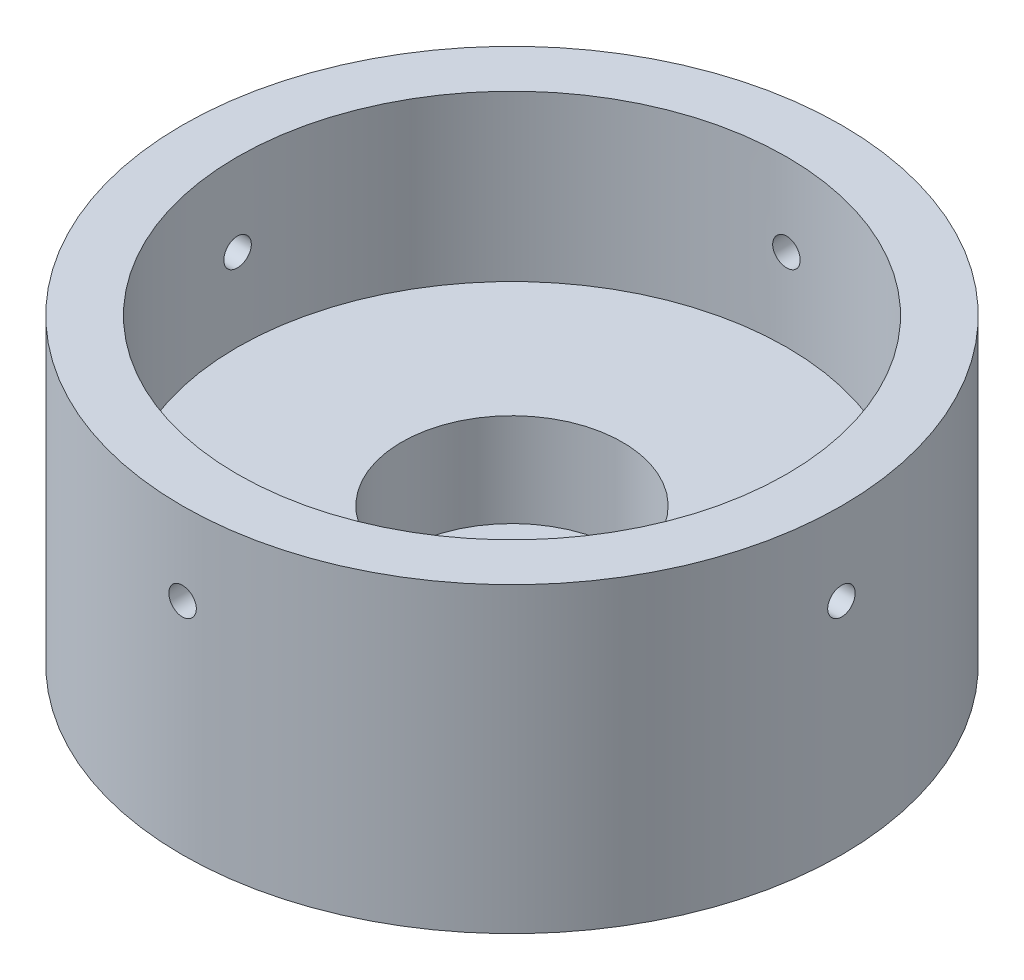
SolidWorks part; units mm, degrees
ref_plane "Front Plane" through (0, 0, 0) normal (0, 0, 1) x (1, 0, 0)
ref_plane "Top Plane" through (0, 0, 0) normal (0, 1, 0) x (1, 0, 0)
ref_plane "Right Plane" through (0, 0, 0) normal (1, 0, 0) x (0, 0, -1)
sketch "Sketch1" plane through (0, 0, 0) normal (0, 1, 0) x (1, 0, 0)
  circle A0 centre (0, 0) radius 60
  dimension "D1" = 120
extrude "Boss-Extrude1" add sketch "Sketch1" along normal blind 35
sketch "Sketch2" plane through (0, 35, 0) normal (0, 1, 0) x (1, 0, 0)
  circle A0 centre (0, 0) radius 20.1
  dimension "D1" = 40.2
extrude "Cut-Extrude1" cut sketch "Sketch2" against normal blind 17
sketch "Sketch3" plane through (0, 0, 0) normal (0, -1, 0) x (1, 0, 0)
  line L1 (-30, -30) -> (30, -30) construction
  line L2 (-30, -30) -> (-30, 30) construction
  line L3 (-30, 30) -> (30, 30) construction
  line L4 (30, -30) -> (30, 30) construction
  line L5 (-30, -30) -> (30, 30) construction
  line L6 (-30, 30) -> (30, -30) construction
  circle A0 centre (-30, 30) radius 3
  circle A1 centre (30, 30) radius 3
  circle A2 centre (30, -30) radius 3
  circle A3 centre (-30, -30) radius 3
  point P0 (0, 0)
  dimension "D3" = 6
  dimension "D1" = 60
  dimension "D2" = 60
extrude "Cut-Extrude2" cut sketch "Sketch3" against normal blind 10
sketch "Sketch5" plane through (0, 35, 0) normal (0, 1, 0) x (1, 0, 0)
  circle A0 centre (0, 0) radius 50
  dimension "D1" = 100
extrude "Cut-Extrude3" cut sketch "Sketch5" against normal blind 10
other "Move Face1" face at (0, 35, 50) parameters "D1"=20
other "Move Face4" face at (0, 18, 20.1) parameters "D1"=10
sketch "Sketch6" plane through (0, 0, 0) normal (1, 0, 0) x (0, 0, -1)
  line L0 (0, 55) -> (0, 40) construction
  line L1 (60, 55) -> (-60, 55) construction
  circle A0 centre (0, 40) radius 2.5
  dimension "D2" = 5
  dimension "D1" = 15
extrude "Cut-Extrude4" cut sketch "Sketch6" against normal through all both and the other way through all
pattern_circular "CirPattern1" count 2 over 90 about axis through (0, 35, 0) along (0, -1, 0) of "Cut-Extrude4"
